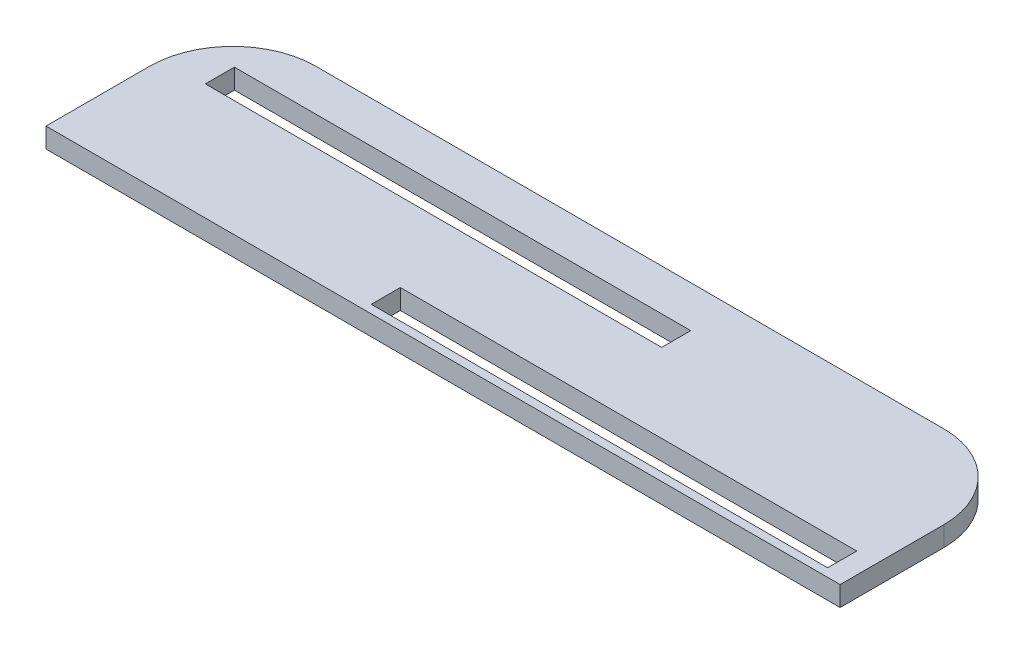
SolidWorks part; units mm, degrees
material "PBT General Purpose"
ref_plane "Front Plane" through (0, 0, 0) normal (0, 0, 1) x (1, 0, 0)
ref_plane "Top Plane" through (0, 0, 0) normal (0, 1, 0) x (1, 0, 0)
ref_plane "Right Plane" through (0, 0, 0) normal (1, 0, 0) x (0, 0, -1)
sketch "Sketch1" plane through (0, 0, 0) normal (0, 1, 0) x (1, 0, 0)
  line L0 (0, 0) -> (0, 2.25)
  line L1 (0, 2.25) -> (9.57, 2.25)
  line L2 (9.57, 2.25) -> (9.57, 0)
  line L3 (9.57, 0) -> (0, 0)
  line L4 (0.52, 1.75) -> (0.52, 1.4)
  line L5 (0.52, 1.4) -> (6.02, 1.4)
  line L6 (6.02, 1.4) -> (6.02, 1.75)
  line L7 (6.02, 1.75) -> (0.52, 1.75)
  line L8 (3.82, 0.45) -> (3.82, 0.1)
  line L9 (3.82, 0.1) -> (9.32, 0.1)
  line L10 (9.32, 0.1) -> (9.32, 0.45)
  line L11 (9.32, 0.45) -> (3.82, 0.45)
  dimension "D1" = 5.5
  dimension "D2" = 5.5
  dimension "D3" = 0.35
  dimension "D4" = 0.35
  dimension "D5" = 0.95
  dimension "D6" = 2.2
  dimension "D7" = 0.1
  dimension "D8" = 0.5
  dimension "D9" = 0.25
  dimension "D10" = 0.52
extrude "Boss-Extrude1" add sketch "Sketch1" along normal blind 0.24
fillet "Fillet1" radius 1 2 edges at (9.57, 0.12, -2.25) (0, 0.12, -2.25)
